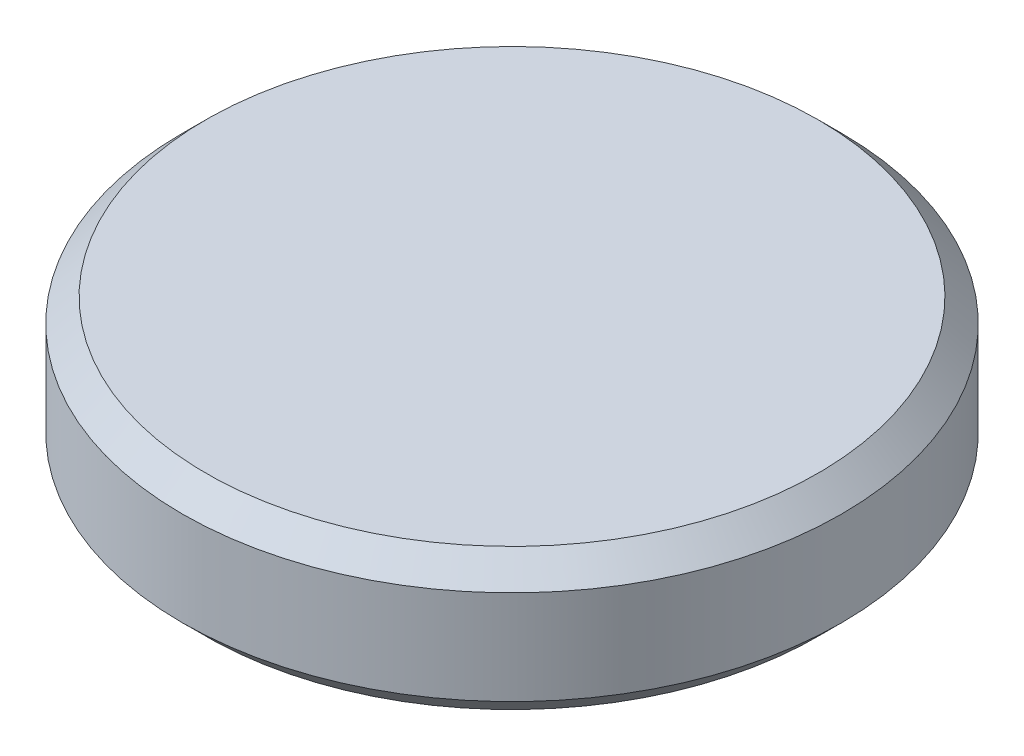
SolidWorks part; units mm, degrees
material "AISI 1015 Steel, Cold Drawn (SS)"
ref_plane "Front Plane" through (0, 0, 0) normal (0, 0, 1) x (1, 0, 0)
ref_plane "Top Plane" through (0, 0, 0) normal (0, 1, 0) x (1, 0, 0)
ref_plane "Right Plane" through (0, 0, 0) normal (1, 0, 0) x (0, 0, -1)
sketch "Sketch1" plane through (0, 0, 0) normal (0, 0, 1) x (1, 0, 0)
  line L0 (0, 0) -> (6.5, 0)
  line L1 (7, -0.5) -> (7, -2.5)
  line L2 (6.5, -3) -> (1.5, -3)
  line L3 (1.5, -3) -> (1.5, -6)
  line L4 (1.5, -6) -> (0, -6)
  line L5 (0, -6) -> (0, 0)
  line L6 (6.5, 0) -> (7, -0.5)
  line L7 (7, -2.5) -> (6.5, -3)
  line L8 (0, -9.893) -> (0, 4.3644) construction
  point P1 (7, 0)
  point P4 (7, -3)
  dimension "D1" = 7
  dimension "D2" = 1.5
  dimension "D3" = 3
  dimension "D4" = 3
revolve "Revolve1" add sketch "Sketch1" angle 360 about L8
